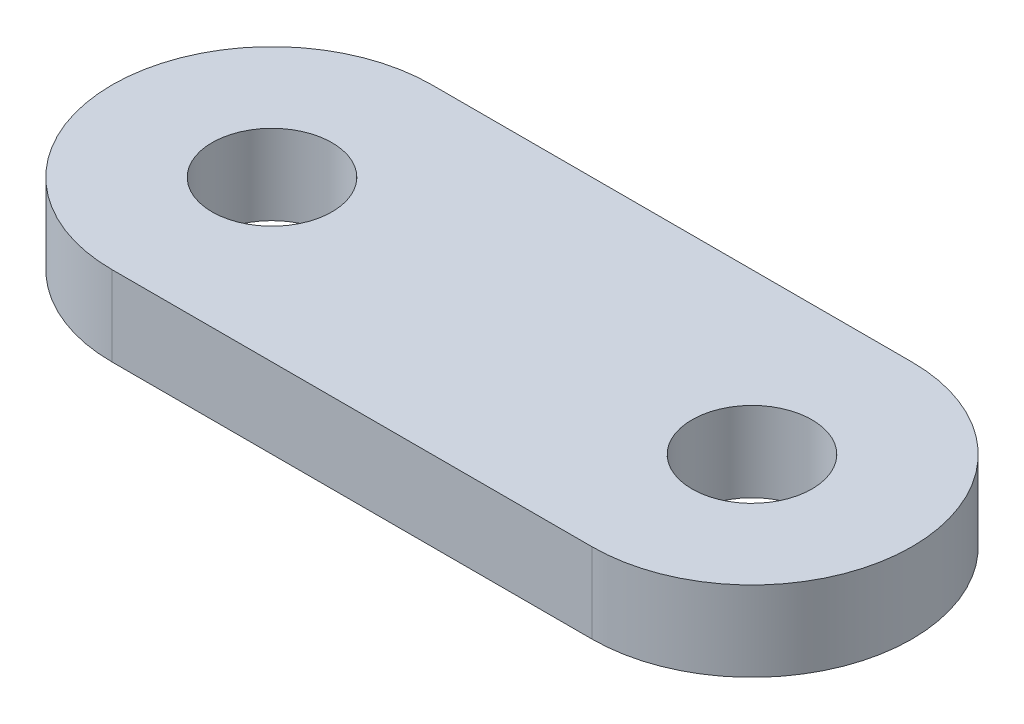
SolidWorks part; units mm, degrees
ref_plane "Front Plane" through (0, 0, 0) normal (0, 0, 1) x (1, 0, 0)
ref_plane "Top Plane" through (0, 0, 0) normal (0, 1, 0) x (1, 0, 0)
ref_plane "Right Plane" through (0, 0, 0) normal (1, 0, 0) x (0, 0, -1)
sketch "Sketch1" plane through (0, 0, 0) normal (0, 1, 0) x (1, 0, 0)
  line L1 (30, -20) -> (-30, -20)
  line L3 (30, 20) -> (-30, 20)
  arc A0 (-30, 20) -> (-30, -20) centre (-30, 0) ccw
  circle A1 centre (-30, 0) radius 7.5
  arc A2 (30, -20) -> (30, 20) centre (30, 0) ccw
  circle A3 centre (30, 0) radius 7.5
  point P0 (0, 0)
extrude "Boss-Extrude1" add sketch "Sketch1" along normal blind 10
